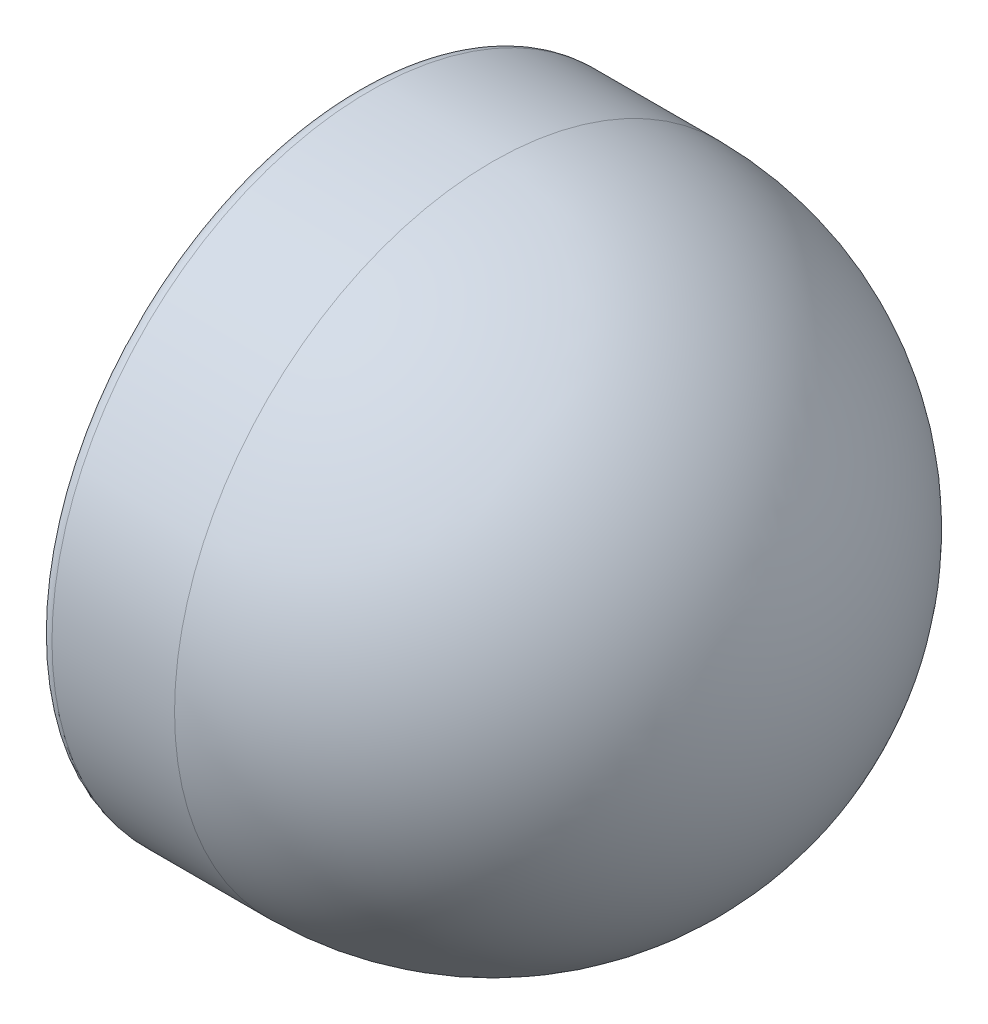
SolidWorks part; units mm, degrees
ref_plane "Front Plane" through (0, 0, 0) normal (0, 0, 1) x (1, 0, 0)
ref_plane "Top Plane" through (0, 0, 0) normal (0, 1, 0) x (1, 0, 0)
ref_plane "Right Plane" through (0, 0, 0) normal (1, 0, 0) x (0, 0, -1)
sketch "Sketch1" plane through (0, 0, 0) normal (0, 0, 1) x (1, 0, 0)
  line L0 (-70, 0) -> (99.4184, 0) construction
  line L1 (-70, 70) -> (-97, 70)
  line L2 (-100, 67) -> (-100, 61.5)
  line L3 (-98.5, 60) -> (-96.6213, 60)
  line L4 (-95.5607, 60.4393) -> (-92, 64)
  line L5 (-70, 69) -> (-97, 69)
  line L6 (-99, 67) -> (-99, 61.5)
  line L7 (-98.5, 61) -> (-96.6213, 61)
  line L8 (-96.2678, 61.1464) -> (-92.7071, 64.7071)
  line L9 (-92, 64) -> (-92, 64.7071)
  line L10 (-92, 64.7071) -> (-92.7071, 64.7071)
  line L11 (-1, 0) -> (0, 0)
  arc A0 (0, 0) -> (-70, 70) centre (-70, 0) ccw
  arc A1 (-97, 70) -> (-100, 67) centre (-97, 67) ccw
  arc A2 (-96.6213, 60) -> (-95.5607, 60.4393) centre (-96.6213, 61.5) ccw
  arc A3 (-100, 61.5) -> (-98.5, 60) centre (-98.5, 61.5) ccw
  arc A4 (-1, 0) -> (-70, 69) centre (-70, 0) ccw
  arc A5 (-97, 69) -> (-99, 67) centre (-97, 67) ccw
  arc A6 (-99, 61.5) -> (-98.5, 61) centre (-98.5, 61.5) ccw
  arc A7 (-96.6213, 61) -> (-96.2678, 61.1464) centre (-96.6213, 61.5) ccw
  point P13 (-100, 70)
  point P16 (-96, 60)
  point P19 (-100, 60)
  dimension "D1" = 70
  dimension "D6" = 3
  dimension "D7" = 1.5
  dimension "D2" = 30
  dimension "D3" = 10
  dimension "D4" = 4
  dimension "D5" = 135
  dimension "D9" = 7
  dimension "D8" = 1
revolve "Revolve1" add sketch "Sketch1" angle 360 about L0
